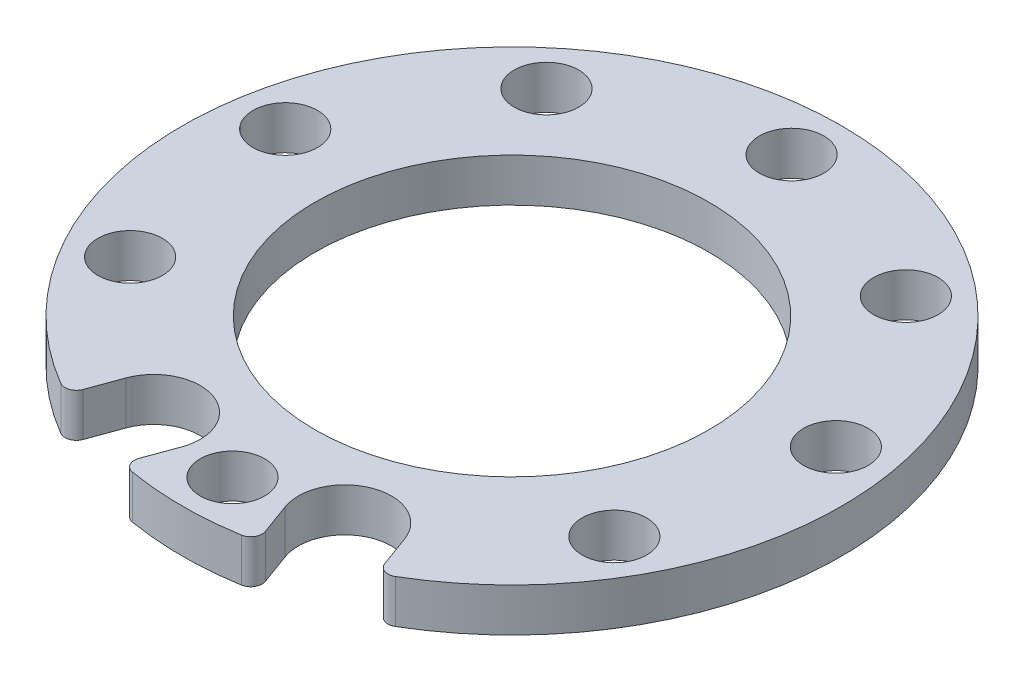
SolidWorks part; units mm, degrees
material "6061-T6 (SS)"
ref_plane "X-Y Datum" through (0, 0, 0) normal (0, 0, 1) x (1, 0, 0)
ref_plane "X-Z Datum" through (0, 0, 0) normal (0, 1, 0) x (1, 0, 0)
ref_plane "Y-Z Datum" through (0, 0, 0) normal (1, 0, 0) x (0, 0, -1)
sketch "Sketch1" plane through (0, 0, 0) normal (0, 1, 0) x (1, 0, 0)
  circle A0 centre (0, 0) radius 45.974
  circle A1 centre (0, 0) radius 39 construction
  circle A2 centre (0, 0) radius 25.908 construction
  circle A3 centre (0, 0) radius 27.4955
  circle A4 centre (-13.3388, -36.648) radius 6.5
  circle A5 centre (13.3388, -36.648) radius 6.5
  point P7 (0, 39)
  point P11 (13.3388, 36.648)
  point P12 (25.0687, 29.8757)
  point P13 (33.775, 19.5)
  point P14 (38.4075, 6.7723)
  point P15 (38.4075, -6.7723)
  point P16 (33.775, -19.5)
  point P17 (25.0687, -29.8757)
  point P18 (13.3388, -36.648)
  point P19 (0, -39)
  point P20 (-13.3388, -36.648)
  point P21 (-25.0687, -29.8757)
  point P22 (-33.775, -19.5)
  point P23 (-38.4075, -6.7723)
  point P24 (-38.4075, 6.7723)
  point P25 (-33.775, 19.5)
  point P26 (-25.0687, 29.8757)
  point P27 (-13.3388, 36.648)
  point P28 (0, 0)
  dimension "D1" = 91.948
  dimension "D2" = 78
  dimension "D3" = 51.816
  dimension "D6" = 13
  dimension "D4" = 1.5875
  dimension "D5" = 18
extrude "Boss-Extrude1" add sketch "Sketch1" along normal blind 6.0477
hole_wizard "M8 Clearance Hole1" positions "Sketch4" profile "Sketch5" hole size "M8" standard "ANSI Metric" end condition through all
sketch "Sketch4" plane through (0, 6.0477, 0) normal (0, 1, 0) x (1, 0, 0)
  point P0 (0, 39)
sketch "Sketch5" plane through (0, 6.0477, -39) normal (1, 0, 0) x (0, 0, 1)
  line L0 (0, 0) -> (0, 6.0477)
  line L1 (0, 6.0477) -> (4.5, 6.0477)
  line L2 (4.5, 6.0477) -> (4.5, 0)
  line L5 (4.5, 0) -> (0, 0)
  line L11 (0, -6.35) -> (0, 107.95) construction
  dimension "Thru Hole Dia." = 9
  dimension "Thru Hole Depth" = 6.0477
pattern_circular "CirPattern1" count 18 over 360 about axis through (0, 6.0477, 0) along (0, -1, 0) skipping 1, 3, 5, 7, 8, 10, 11, 13, 15, 17 of "M8 Clearance Hole1"
sketch "Sketch6" plane through (0, 6.0477, 0) normal (0, 1, 0) x (1, 0, 0)
  line L0 (0, 39) -> (0, -39) construction
  line L1 (-3.3792, -9.2844) -> (-23.2983, -64.0116) construction
  line L2 (-19.4468, -34.4249) -> (-21.6741, -40.5443)
  line L3 (-7.2308, -38.8711) -> (-9.4581, -44.9906)
  circle A0 centre (0, 0) radius 45.974 construction
  circle A1 centre (-13.3388, -36.648) radius 6.5 construction
  circle A2 centre (0, 0) radius 45.974
  circle A3 centre (-13.3388, -36.648) radius 6.5
  point P11 (-13.3388, -36.648)
  point P12 (-13.3388, -36.648)
  point P19 (0, 0)
  dimension "D1" = 20
extrude "Cut-Extrude1" cut sketch "Sketch6" against normal through all
fillet "Fillet1" radius 1.5875 2 edges at (-9.4581, 3.0239, 44.9906) (-21.6741, 3.0239, 40.5443)
mirror "Mirror1" about plane through (0, 0, 0) normal (1, 0, 0) of "Fillet1", "Cut-Extrude1"
